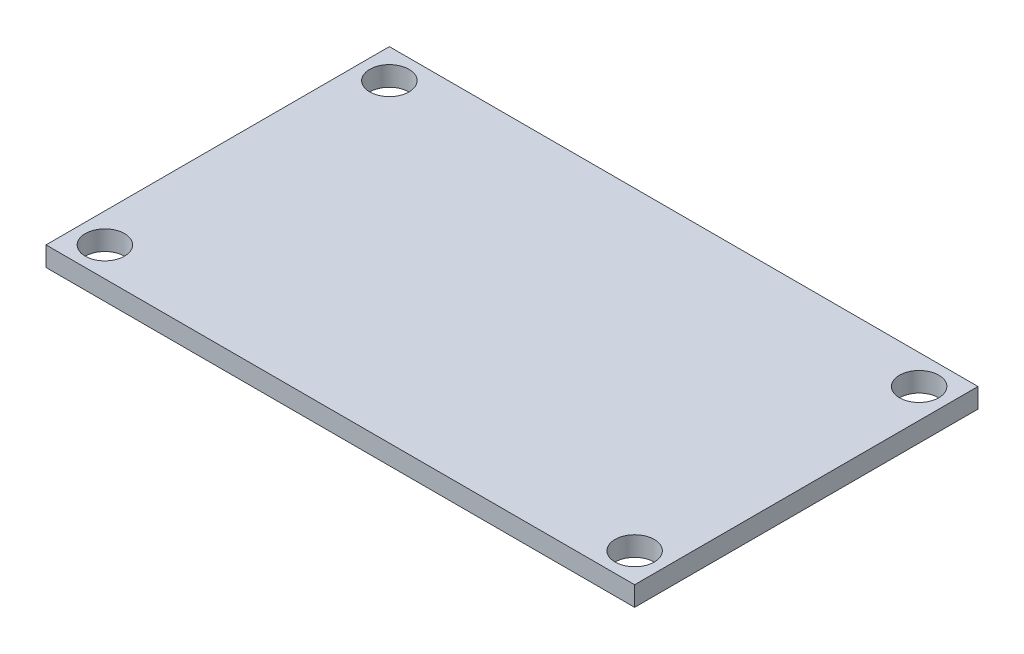
SolidWorks part; units mm, degrees
ref_plane "Front Plane" through (0, 0, 0) normal (0, 0, 1) x (1, 0, 0)
ref_plane "Top Plane" through (0, 0, 0) normal (0, 1, 0) x (1, 0, 0)
ref_plane "Right Plane" through (0, 0, 0) normal (1, 0, 0) x (0, 0, -1)
sketch "Sketch1" plane through (0, 1.6, 0) normal (0, 1, 0) x (1, 0, 0)
  line L0 (80.9821, 72.7508) -> (80.9821, 21.4108) construction
  line L1 (80.9821, 72.7508) -> (80.9821, 21.4108)
  line L2 (80.9821, 47.0808) -> (-70.6179, 47.0808) construction
  line L8 (-20.6179, 35.9048) -> (-20.6179, 68.6708) construction
  line L9 (-100.6179, 29.5808) -> (-40.6179, 29.5808)
  line L10 (-100.6179, 29.5808) -> (-100.6179, 64.5808)
  line L11 (-100.6179, 64.5808) -> (-40.6179, 64.5808)
  line L12 (-40.6179, 29.5808) -> (-40.6179, 64.5808)
  line L13 (-100.6179, 29.5808) -> (-40.6179, 64.5808) construction
  line L14 (-100.6179, 64.5808) -> (-40.6179, 29.5808) construction
  line L15 (-43.6179, 63.5808) -> (-43.6179, 64.5808) construction
  line L16 (-41.6179, 61.5808) -> (-40.6179, 61.5808) construction
  line L17 (-70.6179, 47.0808) -> (-70.6179, 5.734)
  circle A0 centre (-43.6179, 61.5808) radius 2
  circle A1 centre (-43.6179, 32.5808) radius 2
  circle A2 centre (-97.6179, 32.5808) radius 2
  circle A3 centre (-97.6179, 61.5808) radius 2
  dimension "D4" = 4
  dimension "D1" = 35
  dimension "D2" = 60
  dimension "D3" = 20
  dimension "D5" = 1
  dimension "D6" = 1
extrude "Boss-Extrude1" add sketch "Sketch1" against normal blind 2
